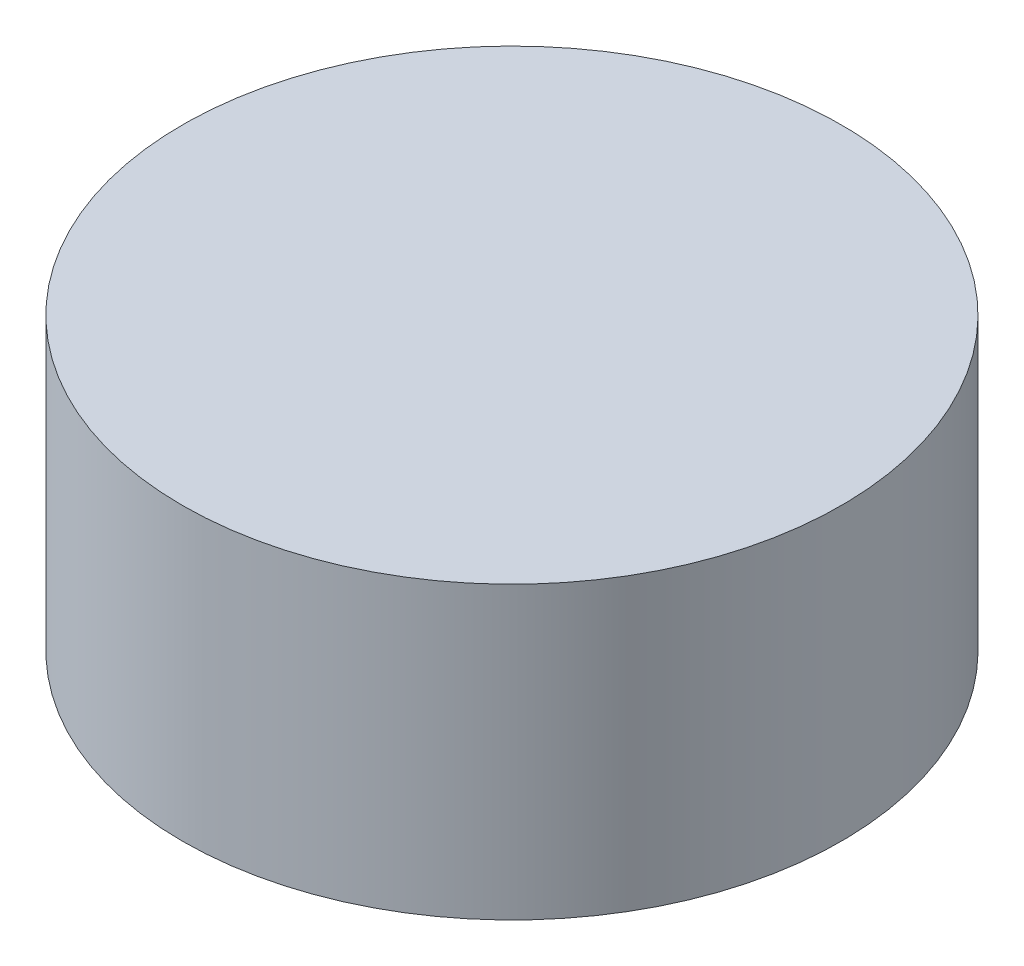
SolidWorks part; units mm, degrees
ref_plane "Спереди" through (0, 0, 0) normal (0, 0, 1) x (1, 0, 0)
ref_plane "Сверху" through (0, 0, 0) normal (0, 1, 0) x (1, 0, 0)
ref_plane "Справа" through (0, 0, 0) normal (1, 0, 0) x (0, 0, -1)
sketch "Эскиз7" plane through (0, 0, 0) normal (0, 1, 0) x (1, 0, 0)
  circle A1 centre (0, 0) radius 17
extrude "Бобышка-Вытянуть6" add sketch "Эскиз7" along normal blind 15 separate body
sketch "Эскиз8" plane through (0, 0, 0) normal (0, -1, 0) x (1, 0, 0)
  circle A1 centre (-5.1, 8.8335) radius 1.5
  circle A5 centre (5.1, 8.8335) radius 1.5
  circle A12 centre (-10.2, 0) radius 1.5
  circle A13 centre (-5.1, -8.8335) radius 1.5
  circle A14 centre (10.2, 0) radius 1.5
  circle A15 centre (5.1, -8.8335) radius 1.5
extrude "Вырез-Вытянуть2" cut sketch "Эскиз8" against normal blind 5
sketch "Эскиз9" plane through (0, 0, 0) normal (0, -1, 0) x (1, 0, 0)
  circle A3 centre (8.6603, 5) radius 2
  circle A4 centre (0, -10) radius 2
  circle A5 centre (-8.6603, 5) radius 2
extrude "Бобышка-Вытянуть7" add sketch "Эскиз9" along normal blind 3.5
